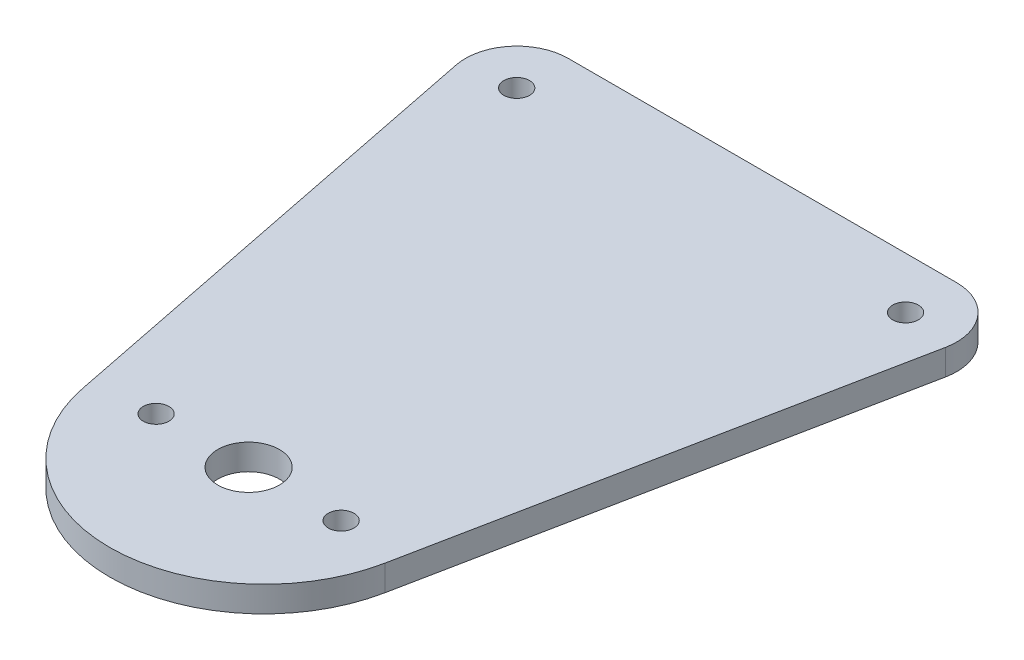
SolidWorks part; units mm, degrees
ref_plane "前视基准面" through (0, 0, 0) normal (0, 0, 1) x (1, 0, 0)
ref_plane "上视基准面" through (0, 0, 0) normal (0, 1, 0) x (1, 0, 0)
ref_plane "右视基准面" through (0, 0, 0) normal (1, 0, 0) x (0, 0, -1)
other "Configuration Table"
sketch "草图2" plane through (0, 0, 0) normal (0, 1, 0) x (1, 0, 0)
  line L0 (-12.17, 178.8675) -> (-12.17, -71.1325) construction
  line L1 (25.632, 178.8675) -> (-49.972, 178.8675)
  line L2 (-59.7778, 166.9064) -> (-41.5874, 75.9546)
  line L3 (17.2474, 75.9546) -> (35.4378, 166.9064)
  line L4 (-42.17, 78.8675) -> (17.83, 78.8675) construction
  line L5 (-49.972, 168.8675) -> (25.632, 168.8675) construction
  arc A0 (-41.5874, 75.9546) -> (17.2474, 75.9546) centre (-12.17, 81.8381) ccw
  arc A1 (25.632, 178.8675) -> (35.4378, 166.9064) centre (25.632, 168.8675) cw
  arc A2 (-49.972, 178.8675) -> (-59.7778, 166.9064) centre (-49.972, 168.8675) ccw
  circle A3 centre (-30.17, 78.8675) radius 2.5
  circle A4 centre (5.83, 78.8675) radius 2.5
  circle A5 centre (-50, 168.8675) radius 2.5
  circle A6 centre (25.66, 168.8675) radius 2.5
  circle A7 centre (-12.17, 78.8675) radius 6
  point P10 (37.83, 178.8675)
  point P13 (-62.17, 178.8675)
  dimension "D3" = 30
  dimension "D5" = 18
  dimension "D6" = 10
  dimension "D7" = 10
  dimension "D8" = 5
  dimension "D9" = 5
  dimension "D11" = 12
  dimension "D1" = 250
  dimension "D2" = 100
  dimension "D4" = 100
  dimension "D10" = 37.83
extrude "凸台-拉伸1" add sketch "草图2" along normal blind 5
equation "\"3mian\"=10"
